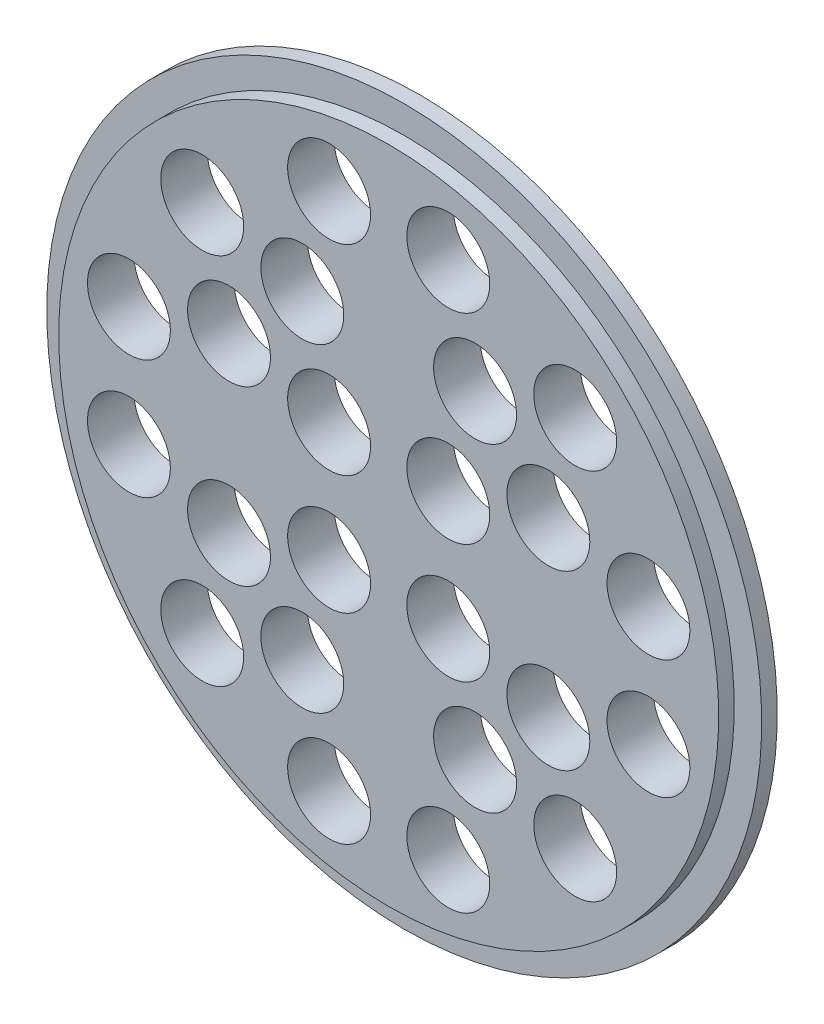
SolidWorks part; units mm, degrees
material "PET"
ref_plane "Front Plane" through (0, 0, 0) normal (0, 0, 1) x (1, 0, 0)
ref_plane "Top Plane" through (0, 0, 0) normal (0, 1, 0) x (1, 0, 0)
ref_plane "Right Plane" through (0, 0, 0) normal (1, 0, 0) x (0, 0, -1)
sketch "Sketch1" plane through (0, 0, 0) normal (0, 0, 1) x (1, 0, 0)
  line L0 (0, 0) -> (-34.5, 0) construction
  line L1 (0, 0) -> (34.5, 0) construction
  line L2 (0, 0) -> (0, -34.5) construction
  line L3 (0, 0) -> (0, 34.5) construction
  line L4 (17.9974, 17.9974) -> (15.4093, 8.3382) construction
  line L5 (15.4093, 8.3382) -> (5.75, 5.75) construction
  line L6 (5.75, 5.75) -> (8.3382, 15.4093) construction
  line L7 (8.3382, 15.4093) -> (17.9974, 17.9974) construction
  line L8 (0, 0) -> (5.75, 5.75) construction
  line L9 (0, 0) -> (5.75, -5.75) construction
  line L10 (8.3382, 15.4093) -> (15.4093, 8.3382) construction
  line L11 (15.4093, 8.3382) -> (25.0685, 5.75) construction
  line L12 (5.75, 25.0685) -> (8.3382, 15.4093) construction
  circle A0 centre (0, 0) radius 34.5
  circle A1 centre (5.75, 5.75) radius 4
  circle A2 centre (8.3382, 15.4093) radius 4
  circle A3 centre (17.9974, 17.9974) radius 4
  circle A4 centre (15.4093, 8.3382) radius 4
  circle A5 centre (25.0685, 5.75) radius 4
  circle A6 centre (5.75, 25.0685) radius 4
  circle A7 centre (25.0686, -5.75) radius 4
  circle A8 centre (15.4093, -8.3382) radius 4
  circle A9 centre (17.9975, -17.9974) radius 4
  circle A10 centre (8.3382, -15.4092) radius 4
  circle A11 centre (5.75, -25.0685) radius 4
  circle A12 centre (5.75, -5.75) radius 4
  circle A13 centre (-5.7499, -25.0685) radius 4
  circle A14 centre (-8.3381, -15.4093) radius 4
  circle A15 centre (-17.9974, -17.9974) radius 4
  circle A16 centre (-15.4092, -8.3382) radius 4
  circle A17 centre (-25.0684, -5.75) radius 4
  circle A18 centre (-5.7499, -5.75) radius 4
  circle A19 centre (-25.0685, 5.75) radius 4
  circle A20 centre (-15.4092, 8.3382) radius 4
  circle A21 centre (-17.9974, 17.9974) radius 4
  circle A22 centre (-8.3382, 15.4092) radius 4
  circle A23 centre (-5.75, 25.0685) radius 4
  circle A24 centre (-5.75, 5.75) radius 4
  dimension "D1" = 69
  dimension "D2" = 8
  dimension "D3" = 5.75
  dimension "D4" = 5.75
  dimension "D5" = 5.75
  dimension "D6" = 150
  dimension "D7" = 5.75
  dimension "D8" = 10
  dimension "D13" = 90
  dimension "D14" = 8.1317
  dimension "D12" = 4
extrude "Boss-Extrude1" add sketch "Sketch1" along normal blind 4.5
sketch "Sketch2" plane through (0, 0, 0) normal (1, 0, 0) x (0, 0, -1)
  line L1 (0, 34.5) -> (-1.5, 34.5)
  line L2 (0, 34.5) -> (0, 31.85)
  line L3 (0, 31.85) -> (-1.5, 31.85)
  line L4 (-1.5, 34.5) -> (-1.5, 31.85)
  line L5 (-4.5, 34.5) -> (-3, 34.5)
  line L6 (-4.5, 34.5) -> (-4.5, 31.85)
  line L7 (-4.5, 31.85) -> (-3, 31.85)
  line L8 (-3, 34.5) -> (-3, 31.85)
  dimension "D1" = 2.65
  dimension "D2" = 1.5
sketch "Sketch3" plane through (0, 0, 0) normal (1, 0, 0) x (0, 0, -1)
  line L0 (0, 0) -> (-4.5, 0) construction
revolve "Cut-Revolve1" cut sketch "Sketch2" angle 360 about L0
sketch "Sketch4" plane through (0, 0, 0) normal (0, 1, 0) x (1, 0, 0)
  line L0 (31.85, 0) -> (-31.85, 0) construction
  line L1 (-0.775, 0) -> (0.775, 0)
  line L2 (-0.775, 0) -> (-0.775, -1.5)
  line L3 (-0.775, -1.5) -> (0.775, -1.5)
  line L4 (0.775, 0) -> (0.775, -1.5)
  line L5 (0, 200000) -> (0, -200004.5) construction
  dimension "D1" = 1.55
  dimension "D2" = 0.775
  dimension "D3" = 1.5
extrude "Cut-Extrude1" cut sketch "Sketch4" against normal through all both and the other way through all
